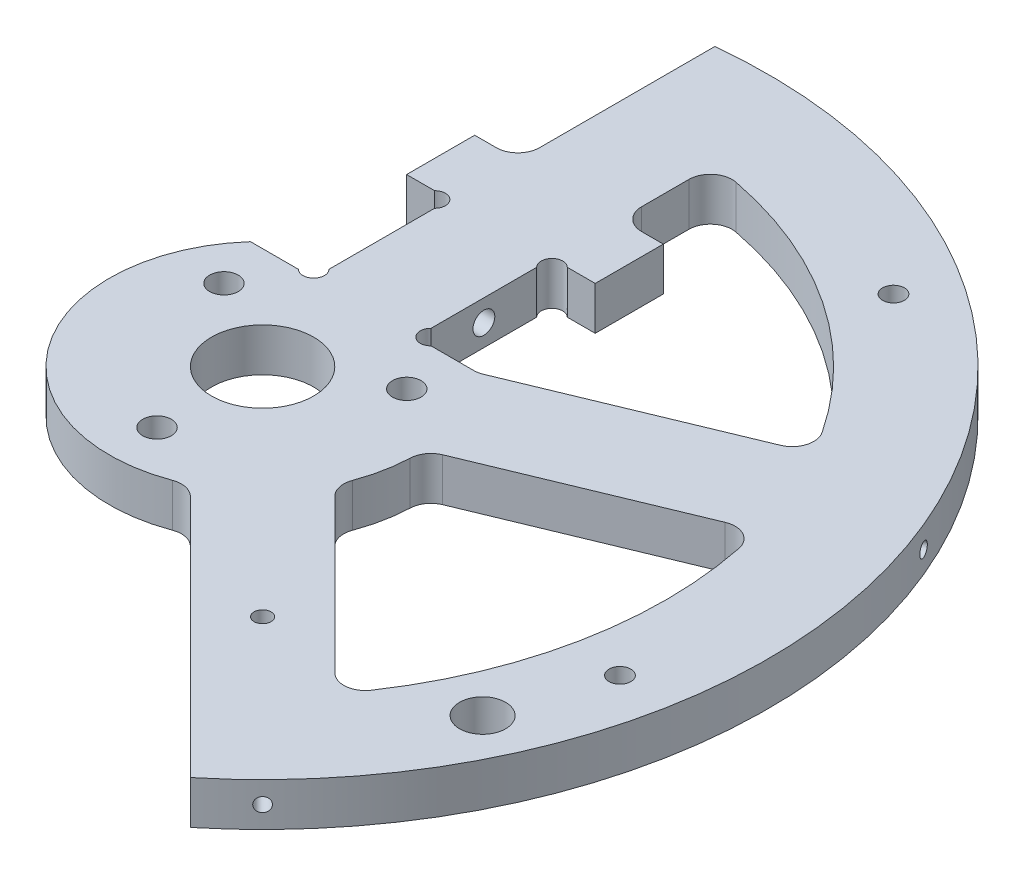
SolidWorks part; units mm, degrees
material "6061 Alloy"
ref_plane "Front Plane" through (0, 0, 0) normal (0, 0, 1) x (1, 0, 0)
ref_plane "Top Plane" through (0, 0, 0) normal (0, 1, 0) x (1, 0, 0)
ref_plane "Right Plane" through (0, 0, 0) normal (1, 0, 0) x (0, 0, -1)
sketch "Sketch1" plane through (0, 0, 0) normal (0, 1, 0) x (1, 0, 0)
  line L0 (0, 0) -> (0, 74.3) construction
  line L1 (0, 0) -> (52.538, -52.538) construction
  line L2 (20.3033, -9.6967) -> (46.898, -36.2914)
  line L3 (7.5, 15) -> (7.5, 35)
  line L4 (-7.5, -3.1066) -> (-5.3033, -5.3033) construction
  line L5 (-7.5, 21.2132) -> (-7.5, 14.1697) construction
  line L6 (-7.5, -3.1066) -> (-7.5, 74.3) construction
  line L7 (7.5, 3.1066) -> (7.5, 74.3) construction
  line L8 (-7.5, -3.1066) -> (47.2347, -57.8413) construction
  line L9 (7.5, 3.1066) -> (57.8413, -47.2347) construction
  line L10 (46.898, -36.2914) -> (57.573, -46.9664) construction
  line L11 (7.5, 58.8238) -> (7.5, 73.9205) construction
  line L12 (0, 0) -> (68.6442, 28.4334) construction
  line L13 (22.4686, 1.1888) -> (57.2162, 15.5818)
  line L14 (-2.8701, 6.9291) -> (0, 8.1179) construction
  line L15 (2.8701, -6.9291) -> (5.7403, -5.7403) construction
  line L16 (2.8701, -6.9291) -> (71.5144, 21.5043) construction
  line L17 (5.7403, -5.7403) -> (13.2403, -2.6336) construction
  line L18 (7.5, 3.1066) -> (13.2403, -2.6336) construction
  line L19 (7.5, 3.1066) -> (7.5, 11.2245) construction
  line L20 (0, 8.1179) -> (7.5, 11.2245) construction
  line L21 (7.5, 11.2245) -> (9.0849, 11.881) construction
  line L22 (-2.8701, 6.9291) -> (65.7741, 35.3625) construction
  line L23 (51.476, 29.44) -> (65.4235, 35.2172) construction
  line L24 (65.4235, 35.2172) -> (65.7741, 35.3625)
  line L25 (57.2162, 15.5818) -> (71.1638, 21.3591) construction
  line L26 (71.1638, 21.3591) -> (71.5144, 21.5043)
  line L27 (13.2403, -2.6336) -> (20.3033, -9.6967) construction
  line L28 (13.85, 5) -> (7.5, 5) construction
  line L29 (13.85, 17.7321) -> (13.85, 15) construction
  line L30 (13.85, 45) -> (7.5, 45)
  line L31 (-13.85, 17.7321) -> (-13.85, 15) construction
  line L32 (13.85, 5) -> (-13.85, 45) construction
  line L33 (13.85, 45) -> (-13.85, 5) construction
  line L34 (-13.85, 35) -> (-7.5, 35)
  line L35 (-13.85, 35) -> (-13.85, 15) construction
  line L36 (-16.7705, 15) -> (-7.5, 15)
  line L37 (-7.5, 35) -> (-7.5, 15)
  line L38 (7.5, 15) -> (16.6148, 15)
  line L39 (7.5, 15) -> (7.5, 35)
  line L40 (7.5, 35) -> (13.85, 35)
  line L41 (13.85, 15) -> (13.85, 35) construction
  line L42 (13.2403, -2.6336) -> (22.4686, 1.1888) construction
  line L43 (7.5, 5) -> (-7.5274, 5) construction
  line L44 (-7.5, 5) -> (-13.85, 5) construction
  line L45 (-7.5274, 5) -> (0, 5) construction
  line L46 (0, 5) -> (-7.5, 5) construction
  line L47 (13.85, 5) -> (13.85, 13.8548) construction
  line L48 (16.6148, 15) -> (16.7283, 15.047)
  line L49 (16.7283, 15.047) -> (51.476, 29.44)
  line L50 (13.85, 13.8548) -> (13.85, 17.7321) construction
  line L51 (9.0849, 11.881) -> (13.85, 13.8548) construction
  line L52 (7.5, 11.2245) -> (7.5, 21.2132) construction
  line L53 (7.5, 21.2132) -> (7.5, 14.1697) construction
  line L54 (-5.3033, -5.3033) -> (9.6967, -20.3033) construction
  line L55 (9.6967, -20.3033) -> (46.9664, -57.573)
  line L56 (-7.5, -3.1066) -> (-7.5, 0) construction
  line L57 (-7.5, 0) -> (-7.5, 5) construction
  line L58 (-13.85, 5) -> (-13.85, 17.7321) construction
  line L59 (-7.5, 5) -> (-7.5, 21.2132) construction
  line L60 (-7.5, 14.1697) -> (-7.5, 15) construction
  line L61 (-7.5, 15) -> (-7.5, 35) construction
  line L62 (-13.85, 15) -> (-13.85, 35) construction
  line L63 (-13.85, 35) -> (-13.85, 45)
  line L64 (13.85, 15) -> (13.85, 35) construction
  line L65 (13.85, 35) -> (13.85, 45)
  line L66 (0, 45) -> (-7.5, 45) construction
  line L67 (-7.5, 45) -> (-13.85, 45)
  line L68 (7.5, 45) -> (0, 45) construction
  line L69 (7.5, 14.1697) -> (7.5, 15) construction
  line L70 (7.5, 35.8303) -> (7.5, 45) construction
  line L71 (7.5, 45) -> (7.5, 58.8238)
  line L72 (7.5, 35) -> (7.5, 35.8303) construction
  line L73 (-7.5, 35) -> (-7.5, 35.8303) construction
  line L74 (-7.5, 45) -> (-7.5, 73.9205)
  line L75 (-7.5, 35.8303) -> (-7.5, 45) construction
  line L77 (13.85, 13.8548) -> (16.6148, 15) construction
  arc A0 (46.9664, -57.573) -> (-7.5, 73.9205) centre (0, 0) ccw
  arc A1 (46.898, -36.2914) -> (57.2162, 15.5818) centre (0, 0) ccw
  arc A2 (-7.5, 73.9205) -> (46.9664, -57.573) centre (0, 0) ccw construction
  circle A3 centre (0, 0) radius 74.3 construction
  arc A4 (41.9314, -41.9314) -> (46.898, -36.2914) centre (0, 0) ccw construction
  circle A5 centre (0, 0) radius 59.3 construction
  arc A6 (36.2914, -46.898) -> (41.9314, -41.9314) centre (0, 0) ccw construction
  arc A7 (-7.5, 58.8238) -> (36.2914, -46.898) centre (0, 0) ccw construction
  arc A8 (7.5, 58.8238) -> (0, 59.3) centre (0, 0) ccw construction
  arc A9 (0, 59.3) -> (-7.5, 58.8238) centre (0, 0) ccw construction
  arc A10 (57.2162, 15.5818) -> (54.7861, 22.6931) centre (0, 0) ccw construction
  arc A11 (51.476, 29.44) -> (7.5, 58.8238) centre (0, 0) ccw
  arc A12 (54.7861, 22.6931) -> (51.476, 29.44) centre (0, 0) ccw construction
  arc A13 (20.3033, -9.6967) -> (22.4686, 1.1888) centre (0, 0) ccw
  circle A14 centre (0, 0) radius 7.5
  arc A15 (9.6967, -20.3033) -> (15.9099, -15.9099) centre (0, 0) ccw construction
  arc A16 (15.9099, -15.9099) -> (20.3033, -9.6967) centre (0, 0) ccw construction
  arc A17 (22.4686, 1.1888) -> (20.7873, 8.6104) centre (0, 0) ccw construction
  arc A18 (16.7283, 15.047) -> (13.85, 17.7321) centre (0, 0) ccw construction
  arc A19 (20.7873, 8.6104) -> (16.7283, 15.047) centre (0, 0) ccw construction
  arc A20 (13.85, 17.7321) -> (1.7801, 22.4295) centre (0, 0) ccw construction
  arc A21 (-7.5, 21.2132) -> (-13.85, 17.7321) centre (0, 0) ccw construction
  arc A22 (1.7801, 22.4295) -> (-13.85, 17.7321) centre (0, 0) ccw construction
  arc A23 (7.5, 21.2132) -> (0, 22.5) centre (0, 0) ccw construction
  arc A24 (0, 22.5) -> (-7.5, 21.2132) centre (0, 0) ccw construction
  arc A25 (-1.7801, 22.4295) -> (-13.85, 17.7321) centre (0, 0) ccw construction
  arc A26 (-16.7705, 15) -> (9.6967, -20.3033) centre (0, 0) ccw
  arc A27 (-13.85, 17.7321) -> (-16.7705, 15) centre (0, 0) ccw construction
  arc A28 (-16.7705, 15) -> (-1.7801, 22.4295) centre (0, 0) ccw construction
  arc A29 (-13.85, 17.7321) -> (-16.7705, 15) centre (0, 0) ccw construction
  arc A30 (-13.85, 17.7321) -> (-16.7705, 15) centre (0, 0) ccw construction
  arc A31 (-16.7705, 15) -> (7.5, 21.2132) centre (0, 0) ccw construction
  point P77 (0, 25)
  dimension "D1" = 148.6
  dimension "D11" = 45
  dimension "D12" = 15
  dimension "D2" = 135
  dimension "D6" = 67.5
  dimension "D9" = 27.7
  dimension "D10" = 40
  dimension "D13" = 5
  dimension "D14" = 10
  dimension "D15" = 10
  dimension "D3" = 7.5
  dimension "D4" = 7.5
  dimension "D5" = 15
  dimension "D7" = 7.5
  dimension "D8" = 7.5
extrude "Boss-Extrude1" add sketch "Sketch1" along normal mid plane 6.35 contours L31 A26 L55 A0 L74 L67 L63 L34 L37 L36 L49 A18 L29 L38 L3 L40 L65 L30 L71 A11 L2 A13 L13 A1 A14
hole_wizard "M5x0.8 Tapped Hole2" positions "Sketch2" profile "Sketch3" tap size "M5x0.8" standard "ANSI Metric" end condition through all
sketch "Sketch2" plane through (0, 3.175, 0) normal (0, 1, 0) x (1, 0, 0)
  line L1 (0, 0) -> (-13.4234, 7.75) construction
  line L3 (13.4234, 7.75) -> (0, 0) construction
  line L4 (0, 0) -> (0, -15.5) construction
  circle A0 centre (0, 0) radius 15.5 construction
  point P10 (-13.4234, 7.75)
  point P12 (13.4234, 7.75)
  point P16 (0, -15.5)
  dimension "D1" = 31
  dimension "D2" = 120
  dimension "D3" = 120
sketch "Sketch3" plane through (0, 3.175, 15.5) normal (1, 0, 0) x (0, 0, 1)
  line L0 (0, 0) -> (0, 6.35)
  line L1 (0, 6.35) -> (2.1, 6.35)
  line L2 (2.1, 6.35) -> (2.1, 0)
  line L5 (2.1, 0) -> (0, 0)
  line L11 (0, -6.35) -> (0, 107.95) construction
  dimension "Thru Tap Drill Dia." = 4.2
  dimension "Thru Tap Drill Depth" = 6.35
ref_plane "Plane1" through (0, 0, -74.3) normal (0, 0, -1) x (-1, 0, 0)
hole_wizard "M2.5x0.45 Tapped Hole1" positions "Sketch4" profile "Sketch5" tap size "M2.5x0.45" standard "ANSI Metric"
sketch "Sketch4" plane through (0, 0, -74.3) normal (0, 0, -1) x (-1, 0, 0)
  point P0 (0, 0)
sketch "Sketch5" plane through (0, 0, -74.3) normal (1, 0, 0) x (0, 1, 0)
  line L0 (0, 0) -> (0, 10.6159)
  line L1 (0, 10.6159) -> (1.025, 10)
  line L2 (1.025, 10) -> (1.025, 0)
  line L5 (1.025, 0) -> (0, 0)
  line L10 (0, 10.6159) -> (-1.025, 10) construction
  line L11 (0, -6.35) -> (0, 107.95) construction
  dimension "Tap Drill Dia." = 2.05
  dimension "Tap Drill Depth" = 10
  dimension "Drill Angle" = 118
pattern_circular "CirPattern1" count 3 over 135 about axis through (0, 3.175, 0) along (0, -1, 0) of "M2.5x0.45 Tapped Hole1"
hole_wizard "M3 Clearance Hole1" positions "Sketch6" profile "Sketch7" hole size "M3" standard "ANSI Metric"
sketch "Sketch6" plane through (-7.5, 0, 0) normal (-1, 0, 0) x (0, 0, 1)
  line L1 (-35, 3.175) -> (-15, 3.175)
  line L2 (-35, 3.175) -> (-35, -3.175)
  line L3 (-35, -3.175) -> (-15, -3.175)
  line L4 (-15, 3.175) -> (-15, -3.175)
  line L5 (-35, 3.175) -> (-15, -3.175) construction
  line L6 (-35, -3.175) -> (-15, 3.175) construction
  point P199 (-25, 0)
sketch "Sketch7" plane through (-7.5, 0, -25) normal (0, 1, 0) x (0, 0, 1)
  line L0 (0, 0) -> (0, 15)
  line L1 (0, 15) -> (1.6, 15)
  line L2 (1.6, 15) -> (1.6, 0)
  line L5 (1.6, 0) -> (0, 0)
  line L11 (0, -6.35) -> (0, 107.95) construction
  dimension "Thru Hole Dia." = 3.2
  dimension "Thru Hole Depth" = 15
hole_wizard "CSK for M3 Flat Head Machine Screw1" positions "Sketch8" profile "Sketch9" countersink size "M3" standard "ANSI Metric" end condition up to next
sketch "Sketch8" plane through (0, -3.175, 0) normal (0, -1, 0) x (-1, 0, 0)
  line L0 (-58.1606, -11.5689) -> (-72.8723, -14.4952) construction
  line L2 (-32.9453, 49.3061) -> (-41.2789, 61.7782) construction
  arc A0 (-57.2162, 15.5818) -> (-46.898, -36.2914) centre (0, 0) ccw construction
  arc A1 (7.5, 73.9205) -> (-46.9664, -57.573) centre (0, 0) ccw construction
  arc A2 (-7.5, 58.8238) -> (-51.476, 29.44) centre (0, 0) ccw construction
  point P19 (-65.5165, -13.032)
  point P21 (-37.1121, 55.5422)
sketch "Sketch9" plane through (37.1121, -3.175, -55.5422) normal (1, 0, 0) x (0, 0, -1)
  line L0 (0, 0) -> (0, 6.35)
  line L1 (0, 6.35) -> (1.6, 6.35)
  line L2 (1.6, 6.35) -> (1.6, 1.55)
  line L3 (1.6, 1.55) -> (3.15, 0)
  line L5 (3.15, 0) -> (0, 0)
  line L6 (-1.6, 1.55) -> (-3.15, 0) construction
  line L11 (0, -6.35) -> (0, 107.95) construction
  dimension "Thru Hole Dia." = 3.2
  dimension "Thru Hole Depth" = 6.35
  dimension "Near C'Sink Dia." = 6.3
  dimension "Near C'Sink Angle" = 90
hole_wizard "M3x0.5 Tapped Hole1" positions "Sketch10" profile "Sketch11" tap size "M3x0.5" standard "ANSI Metric" end condition up to next
sketch "Sketch10" plane through (0, -3.175, 0) normal (0, -1, 0) x (-1, 0, 0)
  line L5 (-9.6967, -20.3033) -> (-46.9664, -57.573) construction
  line L6 (0, 0) -> (-52.538, -52.538) construction
  arc A2 (7.5, 73.9205) -> (-46.9664, -57.573) centre (0, 0) ccw construction
  point P37 (-31.8198, -31.8198)
  dimension "D2" = 45
sketch "Sketch11" plane through (31.8198, -3.175, 31.8198) normal (1, 0, 0) x (0, 0, -1)
  line L0 (0, 0) -> (0, 6.35)
  line L1 (0, 6.35) -> (1.25, 6.35)
  line L2 (1.25, 6.35) -> (1.25, 0)
  line L5 (1.25, 0) -> (0, 0)
  line L11 (0, -6.35) -> (0, 107.95) construction
  dimension "Thru Tap Drill Dia." = 2.5
  dimension "Thru Tap Drill Depth" = 6.35
cosmetic thread "Hole Thread2" parameters "D2"=3
sketch "Sketch12" plane through (0, 3.175, 0) normal (0, 1, 0) x (1, 0, 0)
  line L0 (-13.85, 35) -> (-7.5, 35) construction
  line L1 (-7.5, 35) -> (-7.5, 33.8775)
  line L2 (-7.5, 15) -> (-8.6225, 15)
  line L3 (-7.5, 15) -> (-7.5, 16.1225)
  line L4 (-7.5, 16.1225) -> (-8.6225, 16.1225)
  line L5 (-8.6225, 15) -> (-8.6225, 16.1225)
  line L6 (-7.5, 15) -> (-8.6225, 16.1225) construction
  line L7 (-7.5, 16.1225) -> (-8.6225, 15) construction
  line L8 (-7.5, 35) -> (-8.6225, 35)
  line L9 (-8.6225, 35) -> (-8.6225, 33.8775)
  line L10 (-7.5, 33.8775) -> (-8.6225, 33.8775)
  line L11 (-7.5, 35) -> (-8.6225, 33.8775) construction
  line L12 (-8.6225, 35) -> (-7.5, 33.8775) construction
  line L14 (7.5, 35) -> (8.6225, 35)
  line L15 (7.5, 35) -> (7.5, 33.8775)
  line L16 (7.5, 33.8775) -> (8.6225, 33.8775)
  line L17 (8.6225, 35) -> (8.6225, 33.8775)
  line L18 (7.5, 35) -> (8.6225, 33.8775) construction
  line L19 (7.5, 33.8775) -> (8.6225, 35) construction
  line L20 (7.5, 15) -> (8.6225, 15)
  line L21 (7.5, 15) -> (7.5, 16.1225)
  line L22 (7.5, 16.1225) -> (8.6225, 16.1225)
  line L23 (8.6225, 15) -> (8.6225, 16.1225)
  line L24 (7.5, 15) -> (8.6225, 16.1225) construction
  line L25 (7.5, 16.1225) -> (8.6225, 15) construction
  circle A0 centre (-8.6225, 16.1225) radius 1.5875
  circle A1 centre (-8.6225, 33.8775) radius 1.5875
  circle A2 centre (8.6225, 33.8775) radius 1.5875
  circle A3 centre (8.6225, 16.1225) radius 1.5875
  point P8 (-8.0613, 15.5613)
  point P12 (-8.0613, 34.4387)
  point P21 (8.0613, 34.4387)
  point P26 (8.0613, 15.5613)
  line M33 (16.6148, 15) -> (7.5, 15)
  line M34 (7.5, 15) -> (7.5, 35)
  line M35 (7.5, 35) -> (13.85, 35)
  line M40 (-7.5, 15) -> (-16.7705, 15)
  line M47 (-13.85, 35) -> (-7.5, 35)
  line M48 (-7.5, 35) -> (-7.5, 15)
  dimension "D1" = 3.175
extrude "Cut-Extrude1" cut sketch "Sketch12" against normal up to next contours A0 M48 | A0 M40 | A3 M33 | A3 M34 | A2 M34 | A2 M35 | A1 M48 | A1 M47
fillet "Fillet1" radius 3.175 10 edges at (9.6967, 0, 20.3033) (22.4686, 0, -1.1888) (57.2162, 0, -15.5818) (46.898, 0, 36.2914) (20.3033, 0, 9.6967) (51.476, 0, -29.44) (16.6148, 0, -15) (7.5, 0, -45) (7.5, 0, -58.8238) (-7.5, 0, -45)
hole_wizard "1/4 Clearance Hole1" positions "Sketch13" profile "Sketch14" hole size "1/4" standard "ANSI Inch" end condition up to next
sketch "Sketch13" plane through (0, 3.175, 0) normal (0, 1, 0) x (1, 0, 0)
  line L1 (53.7441, -25.0613) -> (67.3387, -31.4005) construction
  line L2 (11.2081, -21.8147) -> (46.9664, -57.573) construction
  arc A2 (46.9664, -57.573) -> (-7.5, 73.9205) centre (0, 0) ccw construction
  arc A3 (49.1414, -33.1906) -> (58.1022, 11.8585) centre (0, 0) ccw construction
  point P85 (60.5414, -28.2309)
  dimension "D1" = 20
sketch "Sketch14" plane through (60.5414, 3.175, 28.2309) normal (1, 0, 0) x (0, 0, 1)
  line L0 (0, 0) -> (0, 6.35)
  line L1 (0, 6.35) -> (3.3782, 6.35)
  line L2 (3.3782, 6.35) -> (3.3782, 0)
  line L5 (3.3782, 0) -> (0, 0)
  line L11 (0, -6.35) -> (0, 107.95) construction
  dimension "Thru Hole Dia." = 6.7564
  dimension "Thru Hole Depth" = 6.35
